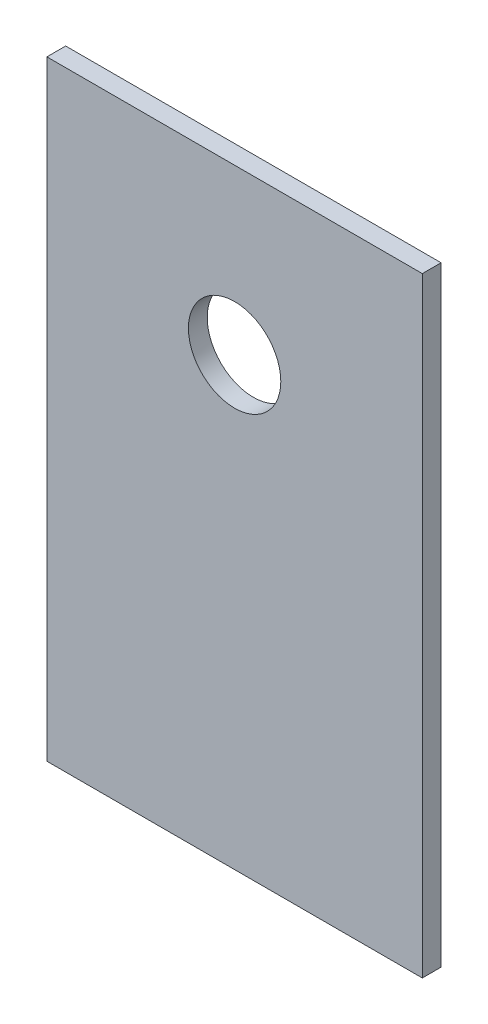
SolidWorks part; units mm, degrees
ref_plane "Front Plane" through (0, 0, 0) normal (0, 0, 1) x (1, 0, 0)
ref_plane "Top Plane" through (0, 0, 0) normal (0, 1, 0) x (1, 0, 0)
ref_plane "Right Plane" through (0, 0, 0) normal (1, 0, 0) x (0, 0, -1)
sketch "Sketch1" plane through (0, 0, 0) normal (0, 0, 1) x (1, 0, 0)
  line L1 (-50.8, -82.55) -> (50.8, -82.55)
  line L2 (-50.8, -82.55) -> (-50.8, 82.55)
  line L3 (-50.8, 82.55) -> (50.8, 82.55)
  line L4 (50.8, -82.55) -> (50.8, 82.55)
  line L5 (-50.8, -82.55) -> (50.8, 82.55) construction
  line L6 (-50.8, 82.55) -> (50.8, -82.55) construction
  point P0 (0, 0)
  dimension "D1" = 101.6
  dimension "D2" = 165.1
extrude "Boss-Extrude1" add sketch "Sketch1" along normal blind 5.08
sketch "Sketch3" plane through (0, 0, 5.08) normal (0, 0, 1) x (1, 0, 0)
  line L0 (0, -2.794) -> (0, 2.794) construction
  circle A0 centre (0, 38.1) radius 12.5
  dimension "D1" = 38.1
extrude "Cut-Extrude1" cut sketch "Sketch3" against normal through all both and the other way through all contours A0
